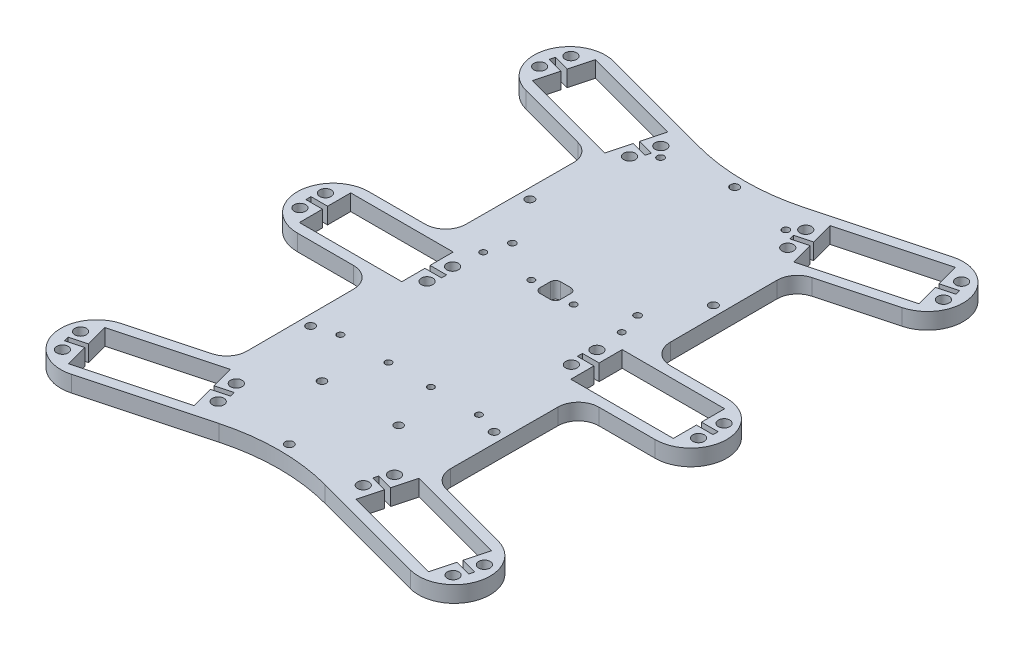
SolidWorks part; units mm, degrees
ref_plane "Front Plane" through (0, 0, 0) normal (0, 0, 1) x (1, 0, 0)
ref_plane "Top Plane" through (0, 0, 0) normal (0, 1, 0) x (1, 0, 0)
ref_plane "Right Plane" through (0, 0, 0) normal (1, 0, 0) x (0, 0, -1)
sketch "Sketch1" plane through (0, 0, 0) normal (0, 1, 0) x (1, 0, 0)
  line L0 (0, 32.1883) -> (0, -21.4181) construction
  line L1 (0, 0) -> (27.1703, 0) construction
  line L2 (-70, 14) -> (-40, 14)
  line L3 (-40, 14) -> (-39.8161, 70)
  line L4 (-39.8161, 70) -> (-73.6235, 79.0587)
  line L5 (-66.3765, 106.1046) -> (0, 88.3191)
  line L10 (-66.3765, 106.1046) -> (-73.6235, 79.0587) construction
  line L12 (-70, 14) -> (-70, -14) construction
  line L14 (-66.3765, -106.1046) -> (0, -88.3191)
  line L15 (-39.8161, -70) -> (-73.6235, -79.0587)
  line L16 (-40, -14) -> (-39.8161, -70)
  line L17 (-70, -14) -> (-40, -14)
  line L18 (66.3765, -106.1046) -> (0, -88.3191)
  line L19 (66.3765, 106.1046) -> (0, 88.3191)
  line L20 (70, 14) -> (70, -14) construction
  line L21 (66.3765, 106.1046) -> (73.6235, 79.0587) construction
  line L22 (70, -14) -> (40, -14)
  line L23 (40, -14) -> (39.8161, -70)
  line L24 (39.8161, -70) -> (73.6235, -79.0587)
  line L25 (39.8161, 70) -> (73.6235, 79.0587)
  line L26 (40, 14) -> (39.8161, 70)
  line L27 (70, 14) -> (40, 14)
  line L28 (-70.4609, 103.1096) -> (-75.6631, 83.6945)
  line L29 (-75.6631, 83.6945) -> (-36.9295, 73.3159)
  line L30 (-36.9295, 73.3159) -> (-31.7272, 92.731)
  line L31 (-31.7272, 92.731) -> (-70.4609, 103.1096)
  line L32 (-51.094, 97.9203) -> (-56.2963, 78.5052) construction
  line L33 (-70, 92.5816) -> (-73.062, 93.4021) construction
  line L34 (-53.12, 10.05) -> (-53.12, -10.05) construction
  line L35 (-73.17, 10.05) -> (-33.07, 10.05)
  line L36 (-73.17, 10.05) -> (-73.17, -10.05)
  line L37 (-73.17, -10.05) -> (-33.07, -10.05)
  line L38 (-33.07, 10.05) -> (-33.07, -10.05)
  line L39 (-73.17, 10.05) -> (-33.07, -10.05) construction
  line L40 (-73.17, -10.05) -> (-33.07, 10.05) construction
  line L41 (-36.9295, -73.3159) -> (-31.7272, -92.731)
  line L42 (-31.7272, -92.731) -> (-70.4609, -103.1096)
  line L43 (-70.4609, -103.1096) -> (-75.6631, -83.6945)
  line L44 (-75.6631, -83.6945) -> (-36.9295, -73.3159)
  line L45 (36.9295, 73.3159) -> (31.7272, 92.731)
  line L46 (75.6631, 83.6945) -> (36.9295, 73.3159)
  line L47 (70.4609, 103.1096) -> (75.6631, 83.6945)
  line L48 (31.7272, 92.731) -> (70.4609, 103.1096)
  line L49 (73.17, -10.05) -> (33.07, 10.05) construction
  line L50 (73.17, 10.05) -> (33.07, -10.05) construction
  line L51 (53.12, 10.05) -> (53.12, -10.05) construction
  line L52 (33.07, 10.05) -> (33.07, -10.05)
  line L53 (73.17, -10.05) -> (33.07, -10.05)
  line L54 (73.17, 10.05) -> (73.17, -10.05)
  line L55 (73.17, 10.05) -> (33.07, 10.05)
  line L56 (36.9295, -73.3159) -> (31.7272, -92.731)
  line L57 (75.6631, -83.6945) -> (36.9295, -73.3159)
  line L58 (31.7272, -92.731) -> (70.4609, -103.1096)
  line L59 (70.4609, -103.1096) -> (75.6631, -83.6945)
  line L60 (-76.4333, 99.4818) -> (-79.0215, 89.8226) construction
  line L61 (-77.7274, 94.6522) -> (-70, 92.5816) construction
  line L62 (-78, 5) -> (-78, -5) construction
  arc A0 (-70, 14) -> (-70, -14) centre (-70, 0) ccw
  arc A1 (-66.3765, 106.1046) -> (-73.6235, 79.0587) centre (-70, 92.5816) ccw
  circle A8 centre (-76.4333, 99.4818) radius 2.25
  circle A9 centre (-79.0215, 89.8226) radius 2.25
  circle A10 centre (-78, 5) radius 2.25
  arc A11 (-66.3765, -106.1046) -> (-73.6235, -79.0587) centre (-70, -92.5816) cw
  circle A12 centre (-79.0215, -89.8226) radius 2.25
  circle A13 centre (-76.4333, -99.4818) radius 2.25
  circle A14 centre (-78, -5) radius 2.25
  circle A15 centre (78, -5) radius 2.25
  circle A16 centre (76.4333, -99.4818) radius 2.25
  circle A17 centre (79.0215, -89.8226) radius 2.25
  arc A18 (66.3765, -106.1046) -> (73.6235, -79.0587) centre (70, -92.5816) ccw
  circle A19 centre (78, 5) radius 2.25
  circle A20 centre (79.0215, 89.8226) radius 2.25
  circle A21 centre (76.4333, 99.4818) radius 2.25
  arc A22 (66.3765, 106.1046) -> (73.6235, 79.0587) centre (70, 92.5816) cw
  arc A23 (70, 14) -> (70, -14) centre (70, 0) cw
  circle A24 centre (-30.957, 76.9437) radius 2.25
  circle A25 centre (-28.3688, 86.603) radius 2.25
  circle A26 centre (-28.24, -5) radius 2.25
  circle A27 centre (-28.24, 5) radius 2.25
  circle A28 centre (-28.3688, -86.603) radius 2.25
  circle A29 centre (-30.957, -76.9437) radius 2.25
  circle A30 centre (28.3688, 86.603) radius 2.25
  circle A31 centre (30.957, 76.9437) radius 2.25
  circle A32 centre (28.24, 5) radius 2.25
  circle A33 centre (28.24, -5) radius 2.25
  circle A34 centre (30.957, -76.9437) radius 2.25
  circle A35 centre (28.3688, -86.603) radius 2.25
  point P60 (-51.094, 97.9203)
  point P62 (-56.2963, 78.5052)
  point P65 (-73.062, 93.4021)
  point P71 (-53.12, 0)
  point P108 (53.12, 0)
  point P118 (-83.523, 96.2051)
  dimension "D2" = 14
  dimension "D3" = 10
  dimension "D8" = 4.5
  dimension "D1" = 75
  dimension "D4" = 70
  dimension "D5" = 30
  dimension "D6" = 35
  dimension "D7" = 56
  dimension "D9" = 8
  dimension "D10" = 5
  dimension "D11" = 10
  dimension "D12" = 40.1
  dimension "D13" = 20.1
  dimension "D14" = 4.83
  dimension "D15" = 40.1
  dimension "D16" = 20.1
  dimension "D17" = 4.83
  dimension "D18" = 8
extrude "Boss-Extrude1" add sketch "Sketch1" along normal blind 6.35
fillet "Fillet1" radius 80 2 edges at (0, 3.175, -88.3191) (0, 3.175, 88.3191)
fillet "Fillet2" radius 8 8 edges at (39.8161, 3.175, 70) (40, 3.175, 14) (40, 3.175, -14) (39.8161, 3.175, -70) (-39.8161, 3.175, -70) (-40, 3.175, -14) (-40, 3.175, 14) (-39.8161, 3.175, 70)
sketch "Sketch5" plane through (0, 6.35, 0) normal (0, 1, 0) x (1, 0, 0)
  line L0 (0, 91.1411) -> (0, -91.1411) construction
  line L1 (-84, 0) -> (84, 0) construction
  line L2 (-33.07, -10.05) -> (-33.07, 10.05) construction
  line L3 (-33.07, 1) -> (-26.57, 1)
  line L4 (-33.07, 1) -> (-33.07, -1)
  line L5 (-33.07, -1) -> (-26.57, -1)
  line L6 (-26.57, 1) -> (-26.57, -1)
  line L7 (-33.07, 1) -> (-26.57, -1) construction
  line L8 (-33.07, -1) -> (-26.57, 1) construction
  line L9 (-33.07, 10.05) -> (-73.17, 10.05) construction
  line L10 (-53.12, 10.05) -> (-53.12, -10.05) construction
  line L11 (-73.17, -10.05) -> (-33.07, -10.05) construction
  line L12 (-73.17, -1) -> (-79.67, 1) construction
  line L13 (-73.17, 1) -> (-79.67, -1) construction
  line L14 (-79.67, 1) -> (-79.67, -1)
  line L15 (-73.17, -1) -> (-79.67, -1)
  line L16 (-73.17, 1) -> (-73.17, -1)
  line L17 (-73.17, 1) -> (-79.67, 1)
  line L18 (-34.0695, 83.9894) -> (-27.791, 82.307)
  line L19 (-36.9295, 73.3159) -> (-31.7272, 92.731) construction
  line L20 (-27.791, 82.307) -> (-28.3087, 80.3752)
  line L21 (-28.3087, 80.3752) -> (-34.5872, 82.0575)
  line L22 (-34.0695, 83.9894) -> (-34.5872, 82.0575)
  line L23 (-51.094, 97.9203) -> (-56.2963, 78.5052) construction
  line L24 (-31.7272, 92.731) -> (-70.4609, 103.1096) construction
  line L25 (-75.6631, 83.6945) -> (-36.9295, 73.3159) construction
  line L26 (-72.8032, 94.368) -> (-73.3208, 92.4362)
  line L27 (-79.5993, 94.1185) -> (-73.3208, 92.4362)
  line L28 (-79.0817, 96.0503) -> (-79.5993, 94.1185)
  line L29 (-72.8032, 94.368) -> (-79.0817, 96.0503)
  line L30 (51.094, 97.9203) -> (56.2963, 78.5052) construction
  line L31 (72.8032, 94.368) -> (79.0817, 96.0503)
  line L32 (79.0817, 96.0503) -> (79.5993, 94.1185)
  line L33 (79.5993, 94.1185) -> (73.3208, 92.4362)
  line L34 (72.8032, 94.368) -> (73.3208, 92.4362)
  line L35 (34.0695, 83.9894) -> (34.5872, 82.0575)
  line L36 (28.3087, 80.3752) -> (34.5872, 82.0575)
  line L37 (27.791, 82.307) -> (28.3087, 80.3752)
  line L38 (34.0695, 83.9894) -> (27.791, 82.307)
  line L39 (73.17, 1) -> (79.67, -1) construction
  line L40 (73.17, -1) -> (79.67, 1) construction
  line L41 (53.12, 10.05) -> (53.12, -10.05) construction
  line L42 (33.07, -1) -> (26.57, 1) construction
  line L43 (33.07, 1) -> (26.57, -1) construction
  line L44 (73.17, 1) -> (79.67, 1)
  line L45 (73.17, 1) -> (73.17, -1)
  line L46 (73.17, -1) -> (79.67, -1)
  line L47 (79.67, 1) -> (79.67, -1)
  line L48 (26.57, 1) -> (26.57, -1)
  line L49 (33.07, -1) -> (26.57, -1)
  line L50 (33.07, 1) -> (33.07, -1)
  line L51 (33.07, 1) -> (26.57, 1)
  line L52 (51.094, -97.9203) -> (56.2963, -78.5052) construction
  line L53 (-51.094, -97.9203) -> (-56.2963, -78.5052) construction
  line L54 (34.0695, -83.9894) -> (27.791, -82.307)
  line L55 (27.791, -82.307) -> (28.3087, -80.3752)
  line L56 (28.3087, -80.3752) -> (34.5872, -82.0575)
  line L57 (34.0695, -83.9894) -> (34.5872, -82.0575)
  line L58 (72.8032, -94.368) -> (73.3208, -92.4362)
  line L59 (79.5993, -94.1185) -> (73.3208, -92.4362)
  line L60 (79.0817, -96.0503) -> (79.5993, -94.1185)
  line L61 (72.8032, -94.368) -> (79.0817, -96.0503)
  line L62 (-72.8032, -94.368) -> (-79.0817, -96.0503)
  line L63 (-79.0817, -96.0503) -> (-79.5993, -94.1185)
  line L64 (-79.5993, -94.1185) -> (-73.3208, -92.4362)
  line L65 (-72.8032, -94.368) -> (-73.3208, -92.4362)
  line L66 (-34.0695, -83.9894) -> (-34.5872, -82.0575)
  line L67 (-28.3087, -80.3752) -> (-34.5872, -82.0575)
  line L68 (-27.791, -82.307) -> (-28.3087, -80.3752)
  line L69 (-34.0695, -83.9894) -> (-27.791, -82.307)
  arc A0 (-20.7055, 93.8671) -> (20.7055, 93.8671) centre (0, 171.1411) ccw construction
  arc A1 (20.7055, -93.8671) -> (-20.7055, -93.8671) centre (0, -171.1411) ccw construction
  arc A2 (-70, 14) -> (-70, -14) centre (-70, 0) ccw construction
  arc A3 (70, -14) -> (70, 14) centre (70, 0) ccw construction
  point P16 (-29.82, 0)
  point P23 (-53.12, 10.05)
  point P34 (-76.42, 0)
  point P39 (-34.3284, 83.0234)
  point P42 (-34.3284, 83.0234)
  point P53 (-73.062, 93.4021)
  point P64 (73.062, 93.4021)
  point P65 (34.3284, 83.0234)
  point P76 (76.42, 0)
  point P77 (29.82, 0)
  point P98 (34.3284, -83.0234)
  point P99 (73.062, -93.4021)
  point P100 (-73.062, -93.4021)
  point P101 (-34.3284, -83.0234)
  dimension "D1" = 2
  dimension "D2" = 6.5
  dimension "D3" = 2
  dimension "D4" = 6.5
extrude "Cut-Extrude2" cut sketch "Sketch5" against normal through all
sketch "Sketch6" plane through (0, 6.35, 0) normal (0, 1, 0) x (1, 0, 0)
  circle A0 centre (27.1, -40.0589) radius 1.25 construction
  circle A1 centre (8.3, -40.0589) radius 1.25 construction
  circle A2 centre (-8.3, -40.0589) radius 1.25 construction
  circle A3 centre (-27.1, -40.0589) radius 1.25 construction
  circle A4 centre (27.1, 15.8411) radius 1.25 construction
  circle A5 centre (-8.3, 15.8411) radius 1.25 construction
  circle A6 centre (-27.1, 15.8411) radius 1.25 construction
  circle A7 centre (-24.5, 24.6411) radius 1.35 construction
  circle A8 centre (24.5, 24.6411) radius 1.35 construction
  circle A9 centre (24.5, 82.6411) radius 1.35 construction
  circle A10 centre (-24.5, 82.6411) radius 1.35 construction
  circle A11 centre (27.1, -40.0589) radius 1.25
  circle A12 centre (8.3, -40.0589) radius 1.25
  circle A13 centre (-8.3, -40.0589) radius 1.25
  circle A14 centre (-27.1, -40.0589) radius 1.25
  circle A15 centre (27.1, 15.8411) radius 1.25
  circle A16 centre (-8.3, 15.8411) radius 1.25
  circle A17 centre (-27.1, 15.8411) radius 1.25
  circle A18 centre (-24.5, 24.6411) radius 1.35
  circle A19 centre (24.5, 24.6411) radius 1.35
  circle A20 centre (24.5, 82.6411) radius 1.35
  circle A21 centre (-24.5, 82.6411) radius 1.35
  circle A22 centre (8.3, 15.8411) radius 1.25 construction
  circle A23 centre (8.3, 15.8411) radius 1.25
extrude "Cut-Extrude3" cut sketch "Sketch6" against normal blind 10
sketch "Sketch8" plane through (0, 6.35, 0) normal (0, 1, 0) x (1, 0, 0)
  circle A0 centre (15, -59.3589) radius 1.6 construction
  circle A1 centre (-15, -59.3589) radius 1.6 construction
  circle A2 centre (15, -59.3589) radius 1.6
  circle A3 centre (-15, -59.3589) radius 1.6
extrude "Cut-Extrude5" cut sketch "Sketch8" against normal blind 10
sketch "Sketch10" plane through (0, 6.35, 0) normal (0, 1, 0) x (1, 0, 0)
  circle A0 centre (-35.905, 42.9071) radius 1.65 construction
  circle A1 centre (0, 87.1411) radius 1.65 construction
  circle A2 centre (35.905, 42.9071) radius 1.65 construction
  circle A3 centre (35.905, -42.9071) radius 1.65 construction
  circle A4 centre (-35.905, -42.9071) radius 1.65 construction
  circle A5 centre (0, -87.1411) radius 1.65 construction
  circle A6 centre (-35.905, 42.9071) radius 1.65
  circle A7 centre (0, 87.1411) radius 1.65
  circle A8 centre (35.905, 42.9071) radius 1.65
  circle A9 centre (35.905, -42.9071) radius 1.65
  circle A10 centre (-35.905, -42.9071) radius 1.65
  circle A11 centre (0, -87.1411) radius 1.65
extrude "Cut-Extrude6" cut sketch "Sketch10" against normal blind 10
sketch "Sketch11" plane through (0, 6.35, 0) normal (0, 1, 0) x (1, 0, 0)
  line L0 (0, 91.1411) -> (0, -91.1411) construction
  line L2 (-4, 21) -> (4, 21)
  line L3 (-4, 21) -> (-4, 13)
  line L4 (-4, 13) -> (4, 13)
  line L5 (4, 21) -> (4, 13)
  line L6 (-4, 21) -> (4, 13) construction
  line L7 (-4, 13) -> (4, 21) construction
  arc A0 (-20.7055, 93.8671) -> (20.7055, 93.8671) centre (0, 171.1411) ccw construction
  arc A1 (20.7055, -93.8671) -> (-20.7055, -93.8671) centre (0, -171.1411) ccw construction
  point P8 (0, 17)
  dimension "D1" = 8
  dimension "D2" = 8
  dimension "D3" = 13
extrude "Cut-Extrude7" cut sketch "Sketch11" against normal blind 10
fillet "Fillet3" radius 2 4 edges at (-4, 3.175, -21) (-4, 3.175, -13) (4, 3.175, -13) (4, 3.175, -21)
